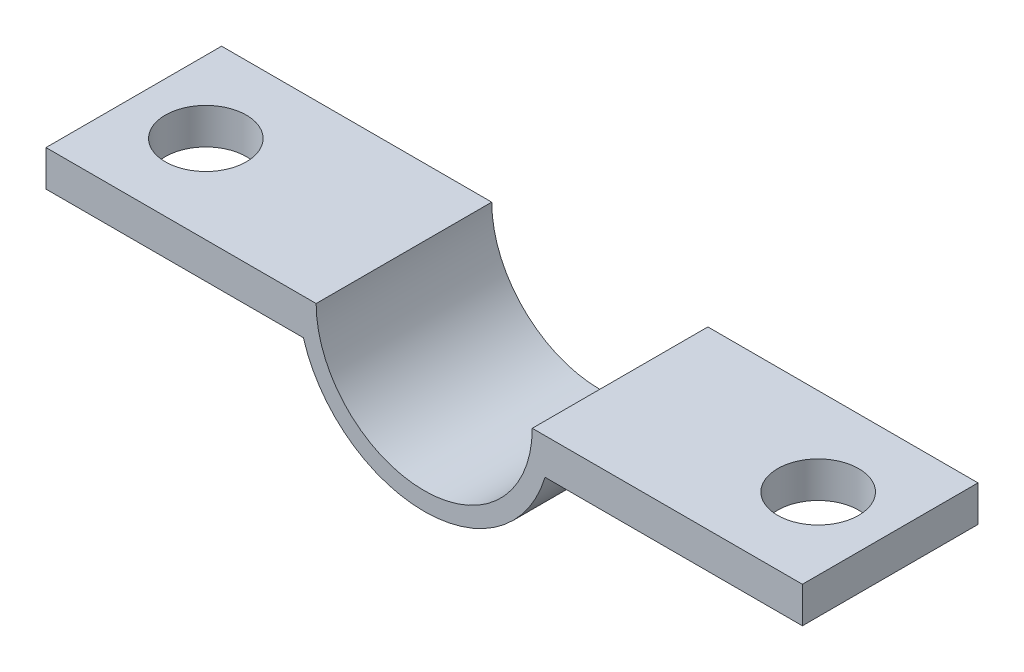
SolidWorks part; units mm, degrees
ref_plane "Front Plane" through (0, 0, 0) normal (0, 0, 1) x (1, 0, 0)
ref_plane "Top Plane" through (0, 0, 0) normal (0, 1, 0) x (1, 0, 0)
ref_plane "Right Plane" through (0, 0, 0) normal (1, 0, 0) x (0, 0, -1)
sketch "Sketch1" plane through (0, 0, 0) normal (0, 0, 1) x (1, 0, 0)
  arc A0 (-6, 0) -> (6, 0) centre (0, 0) ccw
extrude "Extrude-Thin1" add sketch "Sketch1" along normal blind 9.75 thin
sketch "Sketch3" plane through (0, 0, 0) normal (0, 1, 0) x (1, 0, 0)
  line L1 (-21, 0) -> (-6, 0)
  line L2 (-21, 0) -> (-21, -9.75)
  line L3 (-21, -9.75) -> (-6, -9.75)
  line L4 (21, 0) -> (21, -9.75)
  line L5 (6, -9.75) -> (7, -9.75) construction
  line L6 (6, 0) -> (7, 0) construction
  line L7 (-6, 0) -> (-6, -9.75)
  line L8 (6, 0) -> (6, -9.75)
  line L9 (6, 0) -> (21, 0)
  line L10 (6, -9.75) -> (21, -9.75)
  dimension "D1" = 42
extrude "Boss-Extrude1" add sketch "Sketch3" against normal blind 2
sketch "Sketch4" plane through (0, 0, 0) normal (0, 1, 0) x (1, 0, 0)
  line L0 (-21, 0) -> (-21, -9.75) construction
  line L1 (-21, 0) -> (-6, 0) construction
  line L2 (0, -55) -> (0, 55) construction
  circle A0 centre (-17, -4.875) radius 2.25
  circle A1 centre (17, -4.875) radius 2.25
  dimension "D2" = 4.875
  dimension "D1" = 4
extrude "Cut-Extrude1" cut sketch "Sketch4" against normal through all
